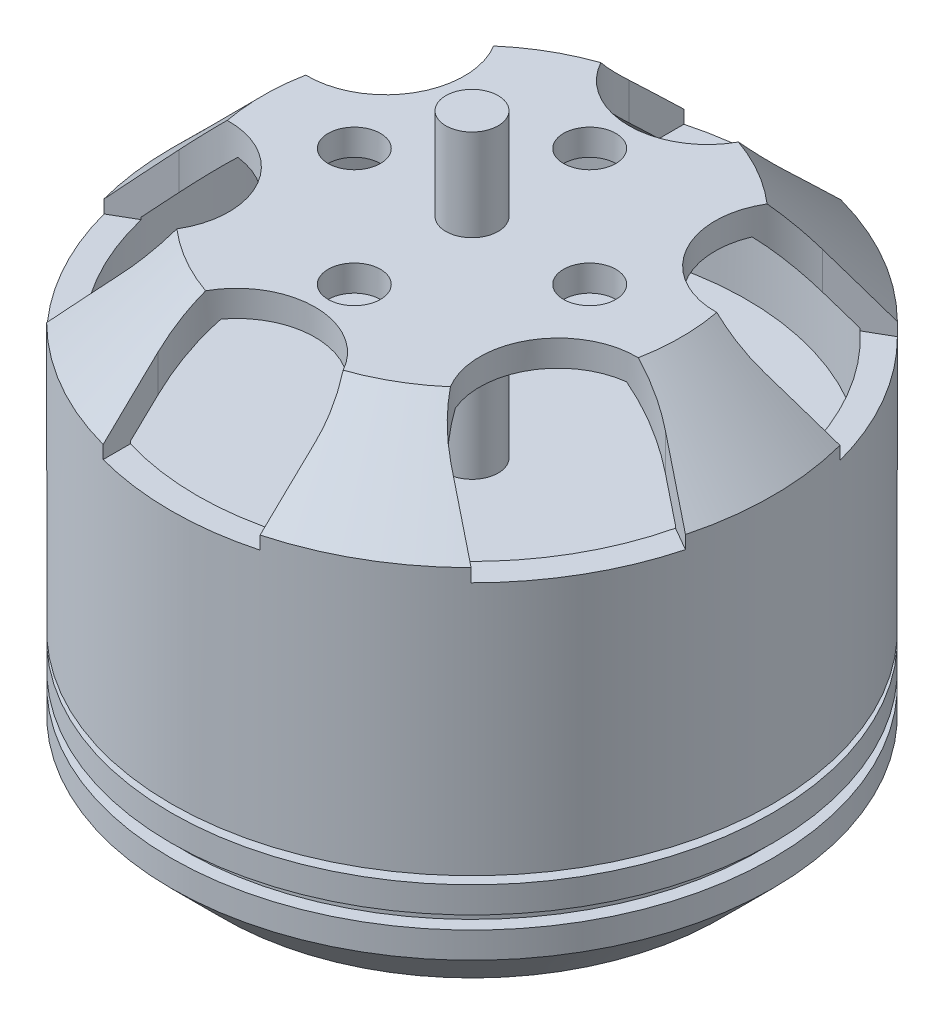
SolidWorks part; units mm, degrees
ref_plane "Front Plane" through (0, 0, 0) normal (0, 0, 1) x (1, 0, 0)
ref_plane "Top Plane" through (0, 0, 0) normal (0, 1, 0) x (1, 0, 0)
ref_plane "Right Plane" through (0, 0, 0) normal (1, 0, 0) x (0, 0, -1)
sketch "Sketch2" plane through (0, 0, 0) normal (0, 0, 1) x (1, 0, 0)
  line L0 (0, 0) -> (1, 0)
  line L1 (1, 0) -> (1, 1.8)
  line L2 (1, 1.8) -> (9.5, 1.8)
  line L3 (9.5, 1.8) -> (11.5, 3.8)
  line L4 (11.5, 3.8) -> (11.5, 4.8)
  line L5 (11.5, 16.8) -> (8, 20.3)
  line L6 (8, 20.3) -> (1, 20.3)
  line L7 (1, 20.3) -> (1, 23.8)
  line L8 (1, 23.8) -> (0, 23.8)
  line L9 (0, 23.8) -> (0, 0)
  line L10 (2, 19.3) -> (7.5858, 19.3)
  line L11 (7.5858, 19.3) -> (10.5, 16.3858)
  line L12 (10.5, 16.3858) -> (10.5, 12.3)
  line L13 (10.5, 12.3) -> (1, 12.3)
  line L14 (1, 12.3) -> (1, 18.3)
  line L15 (1, 18.3) -> (2, 18.3)
  line L16 (2, 18.3) -> (2, 19.3)
  line L17 (11.5, 6.6) -> (9.5, 6.6)
  line L18 (9.5, 6.6) -> (9.5, 6.3)
  line L19 (9.5, 6.3) -> (11.5, 6.3)
  line L20 (11.5, 5.3) -> (11, 5.3)
  line L21 (11, 5.3) -> (11, 4.8)
  line L22 (11, 4.8) -> (11.5, 4.8)
  line L23 (11.5, 5.3) -> (11.5, 6.3)
  line L24 (11.5, 6.6) -> (11.5, 16.8)
  point P24 (10.5, 14.3429)
  dimension "D1" = 1
  dimension "D2" = 1.8
  dimension "D3" = 2
  dimension "D4" = 45
  dimension "D5" = 1
  dimension "D6" = 3.5
  dimension "D7" = 45
  dimension "D8" = 23.8
  dimension "D9" = 11.5
  dimension "D10" = 1
  dimension "D11" = 1
  dimension "D12" = 1
  dimension "D13" = 1
  dimension "D14" = 1
  dimension "D15" = 0.5
  dimension "D16" = 0.5
  dimension "D17" = 2
  dimension "D18" = 0.3
  dimension "D19" = 1
  dimension "D20" = 1
  dimension "D21" = 7
  dimension "D22" = 7
  dimension "D23" = 1
revolve "Revolve1" add sketch "Sketch2" angle 360 about L9
sketch "Sketch3" plane through (0, 20.3, 0) normal (0, 1, 0) x (1, 0, 0)
  line L0 (0, 0) -> (0, 9) construction
  line L1 (-3, 9) -> (-3, 18.5679)
  line L2 (-3, 18.5679) -> (3, 18.5679)
  line L3 (3, 18.5679) -> (3, 9)
  line L4 (6.2942, 7.0981) -> (14.5802, 11.882)
  line L5 (14.5802, 11.882) -> (17.5802, 6.6859)
  line L6 (17.5802, 6.6859) -> (9.2942, 1.9019)
  line L7 (9.2942, -1.9019) -> (17.5802, -6.6859)
  line L8 (17.5802, -6.6859) -> (14.5802, -11.882)
  line L9 (14.5802, -11.882) -> (6.2942, -7.0981)
  line L10 (3, -9) -> (3, -18.5679)
  line L11 (3, -18.5679) -> (-3, -18.5679)
  line L12 (-3, -18.5679) -> (-3, -9)
  line L13 (-6.2942, -7.0981) -> (-14.5802, -11.882)
  line L14 (-14.5802, -11.882) -> (-17.5802, -6.6859)
  line L15 (-17.5802, -6.6859) -> (-9.2942, -1.9019)
  line L16 (-9.2942, 1.9019) -> (-17.5802, 6.6859)
  line L17 (-17.5802, 6.6859) -> (-14.5802, 11.882)
  line L18 (-14.5802, 11.882) -> (-6.2942, 7.0981)
  circle A0 centre (0, 0) radius 4.5 construction
  circle A1 centre (0, 4.5) radius 1
  circle A2 centre (4.5, 0) radius 1
  circle A3 centre (0, -4.5) radius 1
  circle A4 centre (-4.5, 0) radius 1
  arc A5 (-3, 9) -> (3, 9) centre (0, 9) ccw
  arc A6 (6.2942, 7.0981) -> (9.2942, 1.9019) centre (7.7942, 4.5) ccw
  arc A7 (9.2942, -1.9019) -> (6.2942, -7.0981) centre (7.7942, -4.5) ccw
  arc A8 (3, -9) -> (-3, -9) centre (0, -9) ccw
  arc A9 (-6.2942, -7.0981) -> (-9.2942, -1.9019) centre (-7.7942, -4.5) ccw
  arc A10 (-9.2942, 1.9019) -> (-6.2942, 7.0981) centre (-7.7942, 4.5) ccw
  point P6 (0, 0)
  point P15 (0, 0)
  point P16 (0, 0)
  point P45 (0, 0)
  circle M4 centre (0, 0) radius 8
  dimension "D1" = 9
  dimension "D3" = 2
  dimension "D5" = 6
  dimension "D2" = 9
  dimension "D4" = 4
  dimension "D6" = 6
extrude "Cut-Extrude2" cut sketch "Sketch3" against normal blind 4 contours L13 A9 L15 L14 M4 | L16 L17 L18 A10 | A4 | A1 | A2 | A3 | L10 L11 L12 A8 | L9 A7 L7 L8 | L6 A6 L4 L5 | L3 A5 L1 L2
sketch "Sketch6" plane through (0, 1.8, 0) normal (0, -1, 0) x (1, 0, 0)
  circle A0 centre (0, 0) radius 6 construction
  circle A1 centre (0, 0) radius 8 construction
  circle A2 centre (0, 6) radius 1
  circle A3 centre (8, 0) radius 1
  circle A4 centre (0, -6) radius 1
  circle A5 centre (-8, 0) radius 1
  dimension "D1" = 16
  dimension "D2" = 12
  dimension "D3" = 2
extrude "Cut-Extrude3" cut sketch "Sketch6" against normal blind 3
